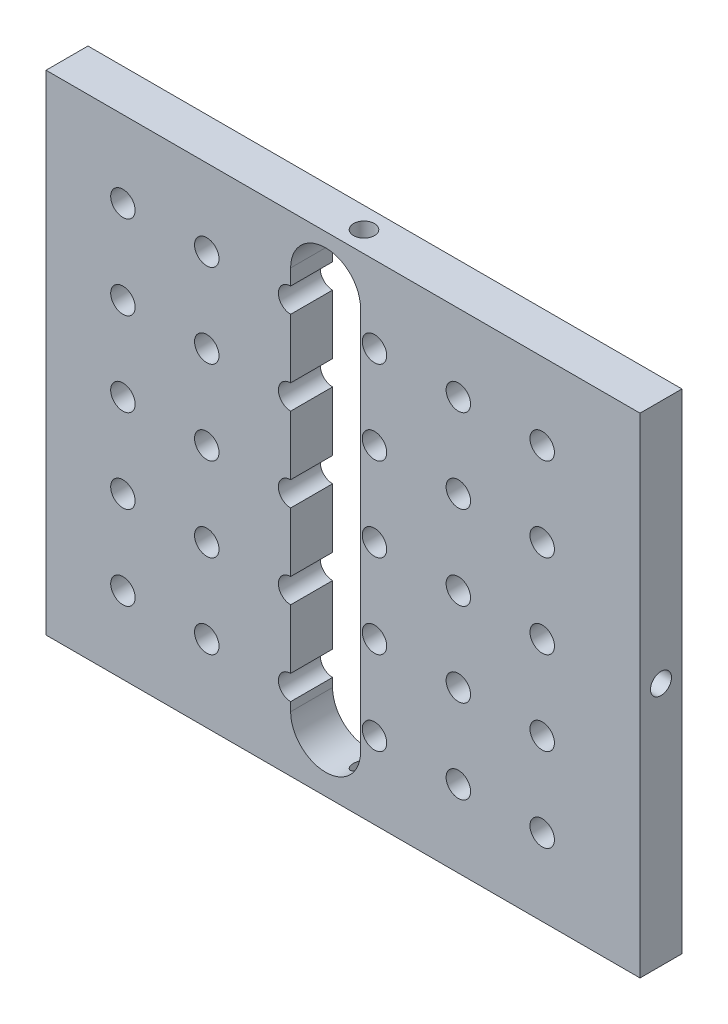
SolidWorks part; units mm, degrees
ref_plane "Plan de face" through (0, 0, 0) normal (0, 0, 1) x (1, 0, 0)
ref_plane "Plan de dessus" through (0, 0, 0) normal (0, 1, 0) x (1, 0, 0)
ref_plane "Plan de droite" through (0, 0, 0) normal (1, 0, 0) x (0, 0, -1)
sketch "Esquisse1" plane through (0, 0, 0) normal (0, 0, 1) x (1, 0, 0)
  line L1 (-42.5, -35) -> (42.5, -35)
  line L2 (-42.5, -35) -> (-42.5, 35)
  line L3 (-42.5, 35) -> (42.5, 35)
  line L4 (42.5, -35) -> (42.5, 35)
  line L5 (-42.5, -35) -> (42.5, 35) construction
  line L6 (-42.5, 35) -> (42.5, -35) construction
  point P0 (0, 0)
  dimension "D1" = 70
  dimension "D2" = 85
extrude "Boss.-Extru.1" add sketch "Esquisse1" along normal blind 6
sketch "Esquisse3" plane through (-42.5, 0, 0) normal (-1, 0, 0) x (0, 0, 1)
  line L0 (-8.5295, 0) -> (14.5295, 0) construction
  line L1 (3, 35) -> (3, -37.4544) construction
  line L2 (6, 35) -> (0, 35) construction
  circle A0 centre (3, 0) radius 1.5
  dimension "D1" = 3
extrude "Enlèv. mat.-Extru.5" cut sketch "Esquisse3" against normal blind 5
mirror "Symétrie1" about plane through (0, 0, 0) normal (1, 0, 0) of "Enlèv. mat.-Extru.5"
sketch "Esquisse5" plane through (0, 0, 0) normal (0, 0, 1) x (1, 0, 0)
  line L0 (-42.5, -35) -> (42.5, -35) construction
  line L2 (-42.5, 35) -> (-42.5, -35) construction
  circle A0 centre (-31.5, -24) radius 1.75
  dimension "D1" = 3.5
  dimension "D2" = 11
  dimension "D3" = 11
extrude "Enlèv. mat.-Extru.6" cut sketch "Esquisse5" along normal up to surface (6 mm away) up to face at (0, 0, 6)
pattern_linear "Répétition linéaire2" count 6 spacing 12 along (1, 0, 0) count 5 spacing 12 along (0, 1, 0) of "Enlèv. mat.-Extru.6"
sketch "Esquisse6" plane through (0, 0, 0) normal (0, 0, 1) x (1, 0, 0)
  line L0 (42.5, -35) -> (42.5, 35) construction
  line L1 (-42.5, -35) -> (42.5, -35) construction
  circle A2 centre (27.5, -20) radius 9.8523
  point P2 (0, 0)
  point P5 (0, 0)
  dimension "D1" = 19.7047
  dimension "D2" = 15
  dimension "D3" = 15
extrude "Enlèv. mat.-Extru.7" [suppressed] cut sketch "Esquisse6" along normal up to surface (6 mm away)
sketch "Esquisse8" plane through (0, 35, 0) normal (0, 1, 0) x (1, 0, 0)
  line L0 (-42.5, -3) -> (46.7621, -3) construction
  line L1 (-42.5, -6) -> (-42.5, 0) construction
  line L2 (0, 7.2443) -> (0, -9.709) construction
  circle A0 centre (0, -3) radius 1.5
  dimension "D1" = 3
extrude "Enlèv. mat.-Extru.8" cut sketch "Esquisse8" against normal blind 5
mirror "Symétrie2" about plane through (0, 0, 0) normal (0, 1, 0) of "Enlèv. mat.-Extru.8"
sketch "Sketch1" plane through (0, 0, 0) normal (0, 0, -1) x (-1, 0, 0)
  line L0 (2.5, -27) -> (2.5, 28) construction
  line L1 (-2.5, -27) -> (-2.5, 28)
  line L2 (7.5, -27) -> (7.5, 28)
  line L4 (42.5, -35) -> (-42.5, -35) construction
  line L5 (-42.5, -35) -> (-42.5, 35) construction
  arc A0 (-2.5, -27) -> (7.5, -27) centre (2.5, -27) ccw
  arc A1 (7.5, 28) -> (-2.5, 28) centre (2.5, 28) ccw
  point P2 (2.5, 0.5)
  point P7 (2.5, -32)
  dimension "D1" = 10
  dimension "D2" = 55
  dimension "D3" = 3
  dimension "D4" = 40
extrude "Cut-Extrude2" cut sketch "Sketch1" against normal through all
